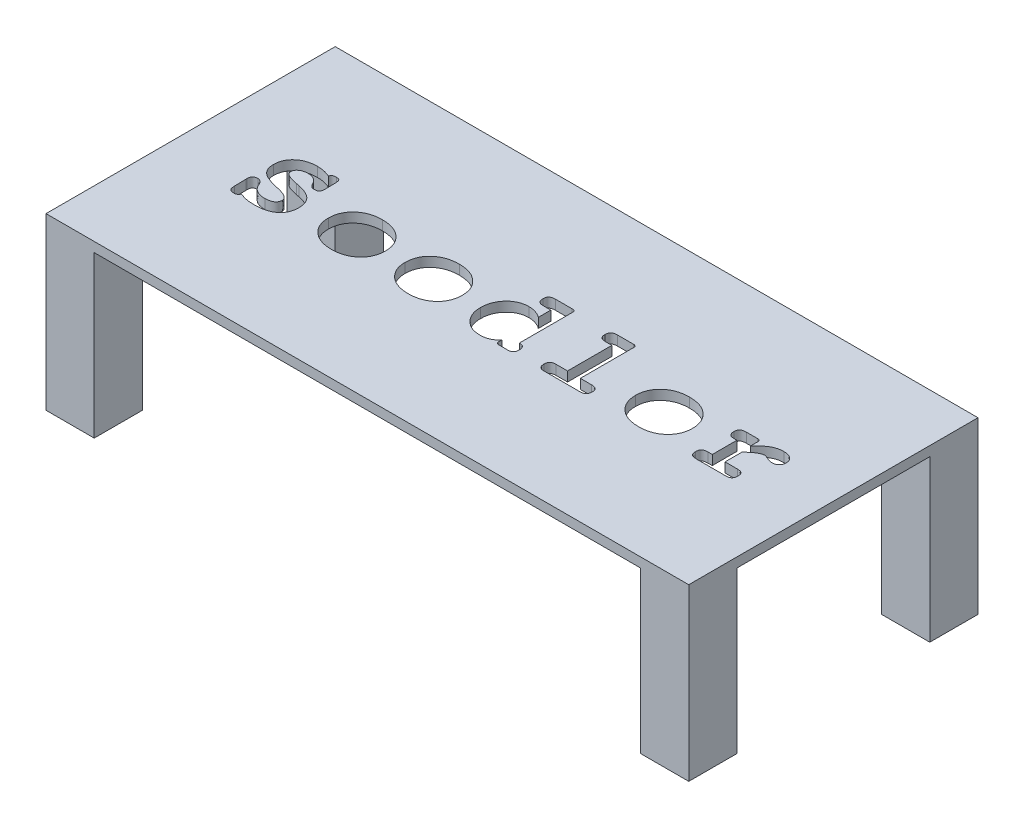
SolidWorks part; units mm, degrees
ref_plane "Front Plane" through (0, 0, 0) normal (0, 0, 1) x (1, 0, 0)
ref_plane "Top Plane" through (0, 0, 0) normal (0, 1, 0) x (1, 0, 0)
ref_plane "Right Plane" through (0, 0, 0) normal (1, 0, 0) x (0, 0, -1)
sketch "Sketch1" plane through (0, 0, 0) normal (0, 1, 0) x (1, 0, 0)
  line L1 (-100, 45) -> (100, 45)
  line L2 (-100, 45) -> (-100, -45)
  line L3 (-100, -45) -> (100, -45)
  line L4 (100, 45) -> (100, -45)
  line L5 (-100, 45) -> (100, -45) construction
  line L6 (-100, -45) -> (100, 45) construction
  point P0 (0, 0)
  dimension "D1" = 90
  dimension "D2" = 200
extrude "Boss-Extrude1" add sketch "Sketch1" along normal blind 3
sketch "Sketch2" plane through (0, 0, 0) normal (0, -1, 0) x (-1, 0, 0)
  line L1 (100, -45) -> (85, -45)
  line L2 (100, -45) -> (100, -30)
  line L3 (100, -30) -> (85, -30)
  line L4 (85, -45) -> (85, -30)
  line L5 (100, 45) -> (85, 45)
  line L6 (100, 45) -> (100, 30)
  line L7 (100, 30) -> (85, 30)
  line L8 (85, 45) -> (85, 30)
  line L9 (-100, -45) -> (-85, -45)
  line L10 (-100, -45) -> (-100, -30)
  line L11 (-100, -30) -> (-85, -30)
  line L12 (-85, -45) -> (-85, -30)
  line L13 (-100, 45) -> (-85, 45)
  line L14 (-100, 45) -> (-100, 30)
  line L15 (-100, 30) -> (-85, 30)
  line L16 (-85, 45) -> (-85, 30)
  dimension "D1" = 15
  dimension "D2" = 15
extrude "Boss-Extrude2" add sketch "Sketch2" along normal blind 50
sketch "Sketch3" plane through (0, 3, 0) normal (0, 1, 0) x (1, 0, 0)
  line L0 (-80, -9.9295) -> (69.7707, -9.9295) construction
  line L3 (-100, 45) -> (-100, -45) construction
  text T0 "<b>Soodlor</b>" font "Courier10 BT" height in points 72
  point P2 (-69.0931, 0)
  point P3 (-31.2367, 0)
  point P4 (51.7164, -13.6531)
  point P5 (33.0985, -7.2403)
  point P7 (-100, 0)
  point P8 (80.057, -6.4128)
  point P9 (0, 0)
  point P10 (-69.7137, -9.9295)
  dimension "D1" = 10
  dimension "D2" = 20
extrude "Cut-Extrude1" cut sketch "Sketch3" against normal blind 10
